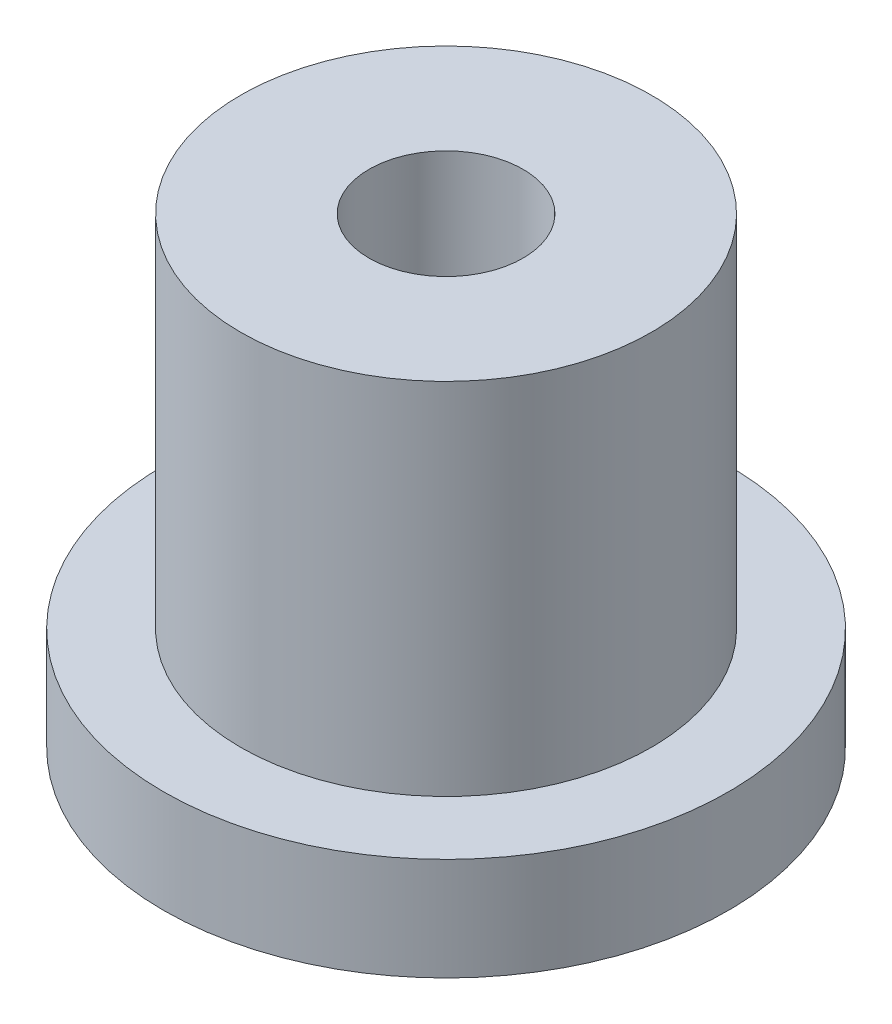
SolidWorks part; units mm, degrees
ref_plane "Front Plane" through (0, 0, 0) normal (0, 0, 1) x (1, 0, 0)
ref_plane "Top Plane" through (0, 0, 0) normal (0, 1, 0) x (1, 0, 0)
ref_plane "Right Plane" through (0, 0, 0) normal (1, 0, 0) x (0, 0, -1)
sketch "Sketch1" plane through (0, 0, 0) normal (0, 1, 0) x (1, 0, 0)
  circle A0 centre (0, 0) radius 5.5
  circle A1 centre (0, 0) radius 1.5
  dimension "D1" = 11
  dimension "D2" = 3
extrude "Boss-Extrude1" add sketch "Sketch1" along normal blind 2
sketch "Sketch2" plane through (0, 2, 0) normal (0, 1, 0) x (1, 0, 0)
  circle A0 centre (0, 0) radius 4
  circle A1 centre (0, 0) radius 1.5 construction
  circle A2 centre (0, 0) radius 1.5
  dimension "D1" = 8
extrude "Boss-Extrude2" add sketch "Sketch2" along normal blind 7
